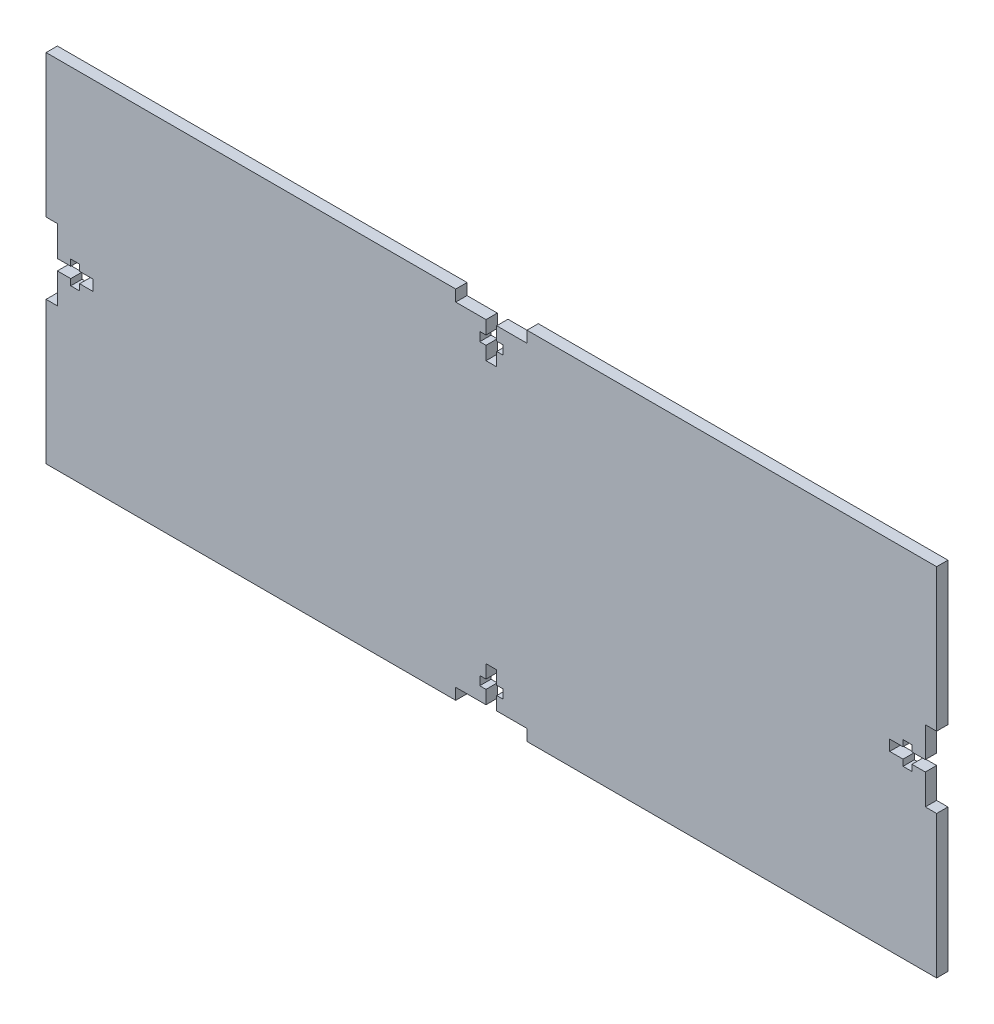
SolidWorks part; units mm, degrees
ref_plane "Front Plane" through (0, 0, 0) normal (0, 0, 1) x (1, 0, 0)
ref_plane "Top Plane" through (0, 0, 0) normal (0, 1, 0) x (1, 0, 0)
ref_plane "Right Plane" through (0, 0, 0) normal (1, 0, 0) x (0, 0, -1)
sketch "Sketch1" plane through (0, 0, 0) normal (0, 0, 1) x (1, 0, 0)
  line L1 (-125, 50) -> (125, 50)
  line L2 (-125, 50) -> (-125, -50)
  line L3 (-125, -50) -> (125, -50)
  line L4 (125, 50) -> (125, -50)
  line L5 (-125, 50) -> (125, -50) construction
  line L6 (-125, -50) -> (125, 50) construction
  point P0 (0, 0)
  dimension "D2" = 100
  dimension "D1" = 250
extrude "Boss-Extrude1" add sketch "Sketch1" along normal blind 3.175
sketch "Sketch5" [suppressed] plane through (-7.3885, -2.5562, 3.175) normal (0, 0, 1) x (1, 0, 0)
  line L1 (-42.6115, 24.3812) -> (-2.6115, 24.3812)
  line L2 (-42.6115, 24.3812) -> (-42.6115, 27.5562)
  line L3 (-42.6115, 27.5562) -> (-2.6115, 27.5562)
  line L4 (-2.6115, 24.3812) -> (-2.6115, 27.5562)
  line L5 (57.3885, 27.5562) -> (-42.6115, 27.5562) construction
  line L7 (57.3885, 24.3812) -> (17.3885, 24.3812)
  line L8 (57.3885, 24.3812) -> (57.3885, 27.5562)
  line L9 (57.3885, 27.5562) -> (17.3885, 27.5562)
  line L10 (17.3885, 24.3812) -> (17.3885, 27.5562)
  line L11 (7.3885, 27.5562) -> (7.3885, 4.502) construction
  circle A0 centre (7.3885, 25.8062) radius 1.4
  dimension "D2" = 2.8
  dimension "D1" = 20
  dimension "D3" = 1.75
  dimension "D4" = 3.175
extrude "Cut-Extrude1" [suppressed] cut sketch "Sketch5" against normal through all
other "Tab<1>" [suppressed]
mirror "Mirror1" [suppressed] about plane through (0, 0, 0) normal (0, 1, 0)
sketch "Sketch59" [suppressed] plane through (52.683, -8.9384, 3.175) normal (0, 0, 1) x (1, 0, 0)
  line L1 (44.142, 30.7634) -> (44.142, 18.9384)
  line L2 (44.142, 30.7634) -> (47.317, 30.7634)
  line L3 (47.317, 30.7634) -> (47.317, 18.9384)
  line L4 (44.142, 18.9384) -> (47.317, 18.9384)
  line L5 (47.317, -12.8866) -> (47.317, 30.7634) construction
  line L7 (44.142, -12.8866) -> (44.142, -1.0616)
  line L8 (44.142, -12.8866) -> (47.317, -12.8866)
  line L9 (47.317, -12.8866) -> (47.317, -1.0616)
  line L10 (44.142, -1.0616) -> (47.317, -1.0616)
  line L11 (47.317, 8.9384) -> (0, 8.9384) construction
  circle A0 centre (45.567, 8.9384) radius 1.4
  dimension "D2" = 2.8
  dimension "D1" = 20
  dimension "D3" = 1.75
  dimension "D4" = 3.175
extrude "Cut-Extrude19" [suppressed] cut sketch "Sketch59" against normal through all
other "Tab<2>" [suppressed]
sketch "Sketch510" [suppressed] plane through (-58.5586, -8.9971, 0) normal (0, 0, -1) x (-1, 0, 0)
  line L1 (38.2664, 30.8221) -> (38.2664, 18.9971)
  line L2 (38.2664, 30.8221) -> (41.4414, 30.8221)
  line L3 (41.4414, 30.8221) -> (41.4414, 18.9971)
  line L4 (38.2664, 18.9971) -> (41.4414, 18.9971)
  line L5 (41.4414, -12.8279) -> (41.4414, 30.8221) construction
  line L7 (38.2664, -12.8279) -> (38.2664, -1.0029)
  line L8 (38.2664, -12.8279) -> (41.4414, -12.8279)
  line L9 (41.4414, -12.8279) -> (41.4414, -1.0029)
  line L10 (38.2664, -1.0029) -> (41.4414, -1.0029)
  line L11 (41.4414, 8.9971) -> (0, 8.9971) construction
  circle A0 centre (39.6914, 8.9971) radius 1.4
  dimension "D2" = 2.8
  dimension "D1" = 20
  dimension "D3" = 1.75
  dimension "D4" = 3.175
extrude "Cut-Extrude110" [suppressed] cut sketch "Sketch510" against normal through all
other "Tab<3>" [suppressed]
sketch "Sketch3" plane through (2.4354, -11.5608, 0) normal (0, 0, -1) x (-1, 0, 0)
  line L0 (-122.5646, 61.5608) -> (-122.5646, -38.4392) construction
  line L1 (-122.5646, 1.5608) -> (-122.5646, 21.5608)
  line L2 (-122.5646, 1.5608) -> (-119.3896, 1.5608)
  line L3 (-119.3896, 1.5608) -> (-119.3896, 10.0608)
  line L4 (-122.5646, 21.5608) -> (-119.3896, 21.5608)
  line L5 (-119.3896, 10.0608) -> (-115.6396, 10.0608)
  line L6 (-115.6396, 10.0608) -> (-115.6396, 8.3108)
  line L7 (-115.6396, 8.3108) -> (-113.1396, 8.3108)
  line L8 (-113.1396, 8.3108) -> (-113.1396, 10.0608)
  line L9 (-113.1396, 10.0608) -> (-109.3896, 10.0608)
  line L10 (-109.3896, 10.0608) -> (-109.3896, 13.0608)
  line L11 (-109.3896, 13.0608) -> (-113.1396, 13.0608)
  line L12 (-113.1396, 13.0608) -> (-113.1396, 14.8108)
  line L13 (-113.1396, 14.8108) -> (-115.6396, 14.8108)
  line L14 (-115.6396, 14.8108) -> (-115.6396, 13.0608)
  line L15 (-115.6396, 13.0608) -> (-119.3896, 13.0608)
  line L16 (-122.5646, 11.5608) -> (-109.3896, 11.5608) construction
  line L17 (-119.3896, 13.0608) -> (-119.3896, 21.5608)
  point P39 (-122.5646, 11.5608)
  dimension "D1" = 3.175
  dimension "D2" = 20
  dimension "D3" = 10
  dimension "D4" = 2.5
  dimension "D5" = 1.75
  dimension "D6" = 3
extrude "T Cut" cut sketch "Sketch3" against normal through all
other "T Cut<1>"
sketch "Sketch32" plane through (-11.5423, -7.3222, 3.175) normal (0, 0, 1) x (1, 0, 0)
  line L0 (-113.4577, 57.3222) -> (-113.4577, -42.6778) construction
  line L1 (-113.4577, -2.6778) -> (-113.4577, 17.3222)
  line L2 (-113.4577, -2.6778) -> (-110.2827, -2.6778)
  line L3 (-110.2827, -2.6778) -> (-110.2827, 5.8222)
  line L4 (-113.4577, 17.3222) -> (-110.2827, 17.3222)
  line L5 (-110.2827, 5.8222) -> (-106.5327, 5.8222)
  line L6 (-106.5327, 5.8222) -> (-106.5327, 4.0722)
  line L7 (-106.5327, 4.0722) -> (-104.0327, 4.0722)
  line L8 (-104.0327, 4.0722) -> (-104.0327, 5.8222)
  line L9 (-104.0327, 5.8222) -> (-100.2827, 5.8222)
  line L10 (-100.2827, 5.8222) -> (-100.2827, 8.8222)
  line L11 (-100.2827, 8.8222) -> (-104.0327, 8.8222)
  line L12 (-104.0327, 8.8222) -> (-104.0327, 10.5722)
  line L13 (-104.0327, 10.5722) -> (-106.5327, 10.5722)
  line L14 (-106.5327, 10.5722) -> (-106.5327, 8.8222)
  line L15 (-106.5327, 8.8222) -> (-110.2827, 8.8222)
  line L16 (-113.4577, 7.3222) -> (-100.2827, 7.3222) construction
  line L17 (-110.2827, 8.8222) -> (-110.2827, 17.3222)
  point P39 (-113.4577, 7.3222)
  dimension "D1" = 3.175
  dimension "D2" = 20
  dimension "D3" = 10
  dimension "D4" = 2.5
  dimension "D5" = 1.75
  dimension "D6" = 3
extrude "T Cut2" cut sketch "Sketch32" against normal through all
other "T Cut<2>"
sketch "Sketch33" plane through (-8.38, 0.2655, 0) normal (0, 0, -1) x (-1, 0, 0)
  line L0 (116.62, 49.7345) -> (-133.38, 49.7345) construction
  line L1 (-18.38, 49.7345) -> (1.62, 49.7345)
  line L2 (-18.38, 49.7345) -> (-18.38, 46.5595)
  line L3 (-18.38, 46.5595) -> (-9.88, 46.5595)
  line L4 (1.62, 49.7345) -> (1.62, 46.5595)
  line L5 (-9.88, 46.5595) -> (-9.88, 42.8095)
  line L6 (-9.88, 42.8095) -> (-11.63, 42.8095)
  line L7 (-11.63, 42.8095) -> (-11.63, 40.3095)
  line L8 (-11.63, 40.3095) -> (-9.88, 40.3095)
  line L9 (-9.88, 40.3095) -> (-9.88, 36.5595)
  line L10 (-9.88, 36.5595) -> (-6.88, 36.5595)
  line L11 (-6.88, 36.5595) -> (-6.88, 40.3095)
  line L12 (-6.88, 40.3095) -> (-5.13, 40.3095)
  line L13 (-5.13, 40.3095) -> (-5.13, 42.8095)
  line L14 (-5.13, 42.8095) -> (-6.88, 42.8095)
  line L15 (-6.88, 42.8095) -> (-6.88, 46.5595)
  line L16 (-8.38, 49.7345) -> (-8.38, 36.5595) construction
  line L17 (-6.88, 46.5595) -> (1.62, 46.5595)
  point P39 (-8.38, 49.7345)
  dimension "D1" = 3.175
  dimension "D2" = 20
  dimension "D3" = 10
  dimension "D4" = 2.5
  dimension "D5" = 1.75
  dimension "D6" = 3
extrude "T Cut3" cut sketch "Sketch33" against normal through all
other "T Cut<3>"
mirror "Mirror2" about plane through (0, 0, 0) normal (0, 1, 0) of "T Cut3"
sketch "Sketch511" [suppressed] plane through (0, 0, 0) normal (0, 0, -1) x (-1, 0, 0)
  circle A0 centre (-15, 0) radius 3.5
  dimension "D1" = 7
  dimension "D2" = 15
extrude "Cut-Extrude111" [suppressed] cut sketch "Sketch511" against normal through all
pattern_linear "LPattern1" [suppressed] count 3 spacing 30 count 2 spacing 30
equation "\"width\"= 250"
equation "\"height\"= 50"
equation "\"depth\"= 100"
equation "\"D2@Sketch1\"     = \"depth\""
equation "\"D1@Sketch1\"= \"width\""
